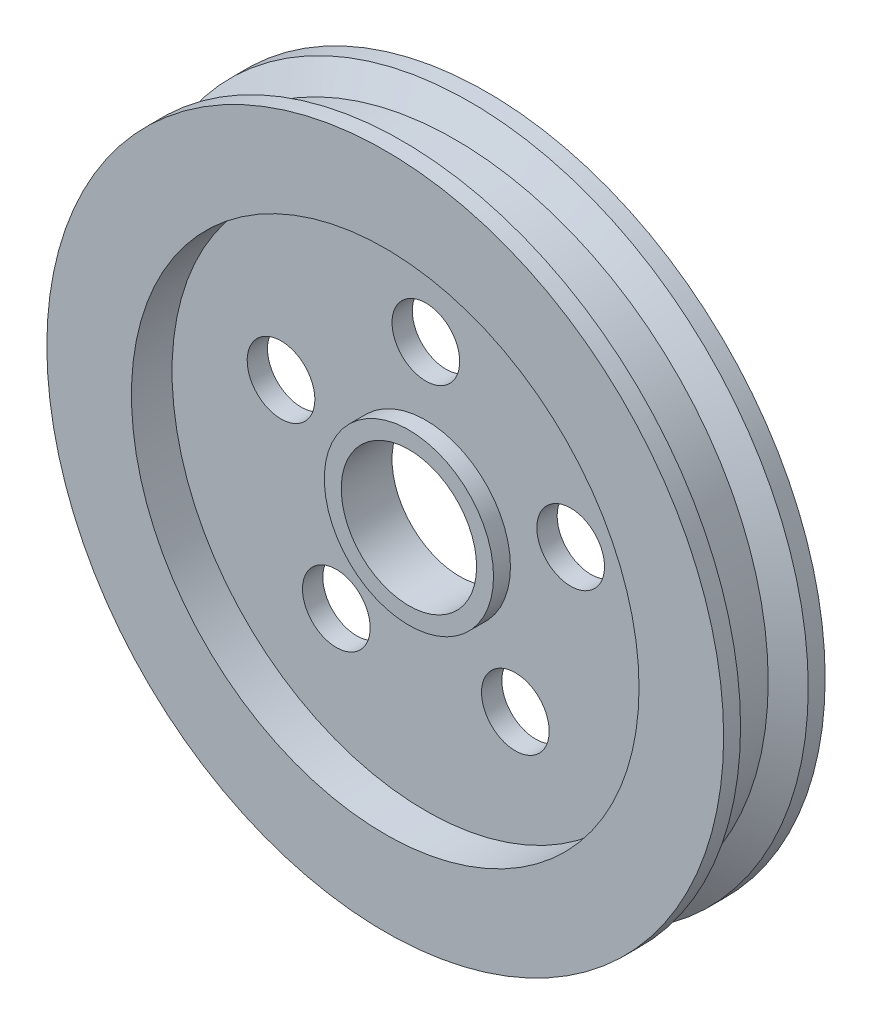
SolidWorks part; units mm, degrees
ref_plane "Front Plane" through (0, 0, 0) normal (0, 0, 1) x (1, 0, 0)
ref_plane "Top Plane" through (0, 0, 0) normal (0, 1, 0) x (1, 0, 0)
ref_plane "Right Plane" through (0, 0, 0) normal (1, 0, 0) x (0, 0, -1)
sketch "Sketch1" plane through (0, 0, 0) normal (0, 0, 1) x (1, 0, 0)
  circle A0 centre (0, 0) radius 4
  circle A1 centre (0, 0) radius 20
  dimension "D1" = 8
  dimension "20" = 40
extrude "Boss-Extrude1" add sketch "Sketch1" along normal mid plane 6
sketch "Sketch3" plane through (0, 0, 3) normal (0, 0, 1) x (1, 0, 0)
  circle A0 centre (0, 0) radius 15
  dimension "D1" = 30
extrude "Cut-Extrude1" cut sketch "Sketch3" against normal blind 2.4 contours A0
mirror "Mirror1" about plane through (0, 0, 0) normal (0, 0, 1) of "Cut-Extrude1"
sketch "Sketch4" plane through (0, 0, 0.6) normal (0, 0, 1) x (1, 0, 0)
  circle A0 centre (0, 9) radius 2
  dimension "D1" = 9
extrude "Cut-Extrude2" cut sketch "Sketch4" against normal through all
pattern_circular "CirPattern1" count 5 over 360 about axis through (0, 0, 0) along (0, 0, 1) of "Cut-Extrude2"
sketch "Sketch5" plane through (0, 0, 0) normal (0, 1, 0) x (1, 0, 0)
  line L0 (0, 0) -> (0, 6.988) construction
  line L1 (20, 2) -> (18.5, 1.134)
  line L2 (20, -3) -> (20, 3) construction
  line L3 (18.5, 1.134) -> (18.5, -1.134)
  line L4 (18.5, -1.134) -> (20, -2)
  line L5 (20, 2) -> (20, -2)
  dimension "D1" = 1.5
  dimension "D2" = 1
  dimension "D3" = 1
  dimension "D4" = 60
  dimension "D5" = 60
revolve "Cut-Revolve1" cut sketch "Sketch5" angle 360 about L0
sketch "Sketch14" plane through (0, 0, 0.6) normal (0, 0, 1) x (1, 0, 0)
  circle A0 centre (0, 0) radius 5
  dimension "D1" = 10
extrude "Boss-Extrude3" add sketch "Sketch14" along normal blind 1 and the other way blind 2 contours A0
sketch "Sketch16" plane through (0, 0, 1.6) normal (0, 0, 1) x (1, 0, 0)
  circle A0 centre (0, 0) radius 4
extrude "Cut-Extrude3" cut sketch "Sketch16" against normal through all
